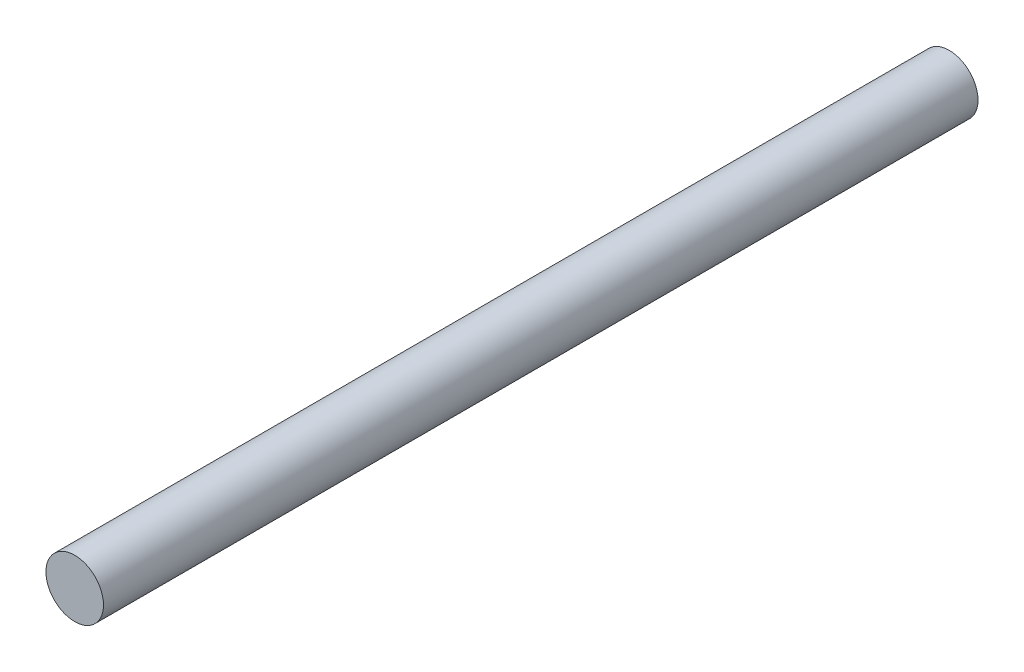
SolidWorks part; units mm, degrees
ref_plane "Front Plane" through (0, 0, 0) normal (0, 0, 1) x (1, 0, 0)
ref_plane "Top Plane" through (0, 0, 0) normal (0, 1, 0) x (1, 0, 0)
ref_plane "Right Plane" through (0, 0, 0) normal (1, 0, 0) x (0, 0, -1)
sketch "Sketch1" plane through (0, 0, 0) normal (0, 0, 1) x (1, 0, 0)
  circle A0 centre (0, 0) radius 2.5
  dimension "D1" = 5
extrude "Boss-Extrude1" add sketch "Sketch1" along normal blind 76
